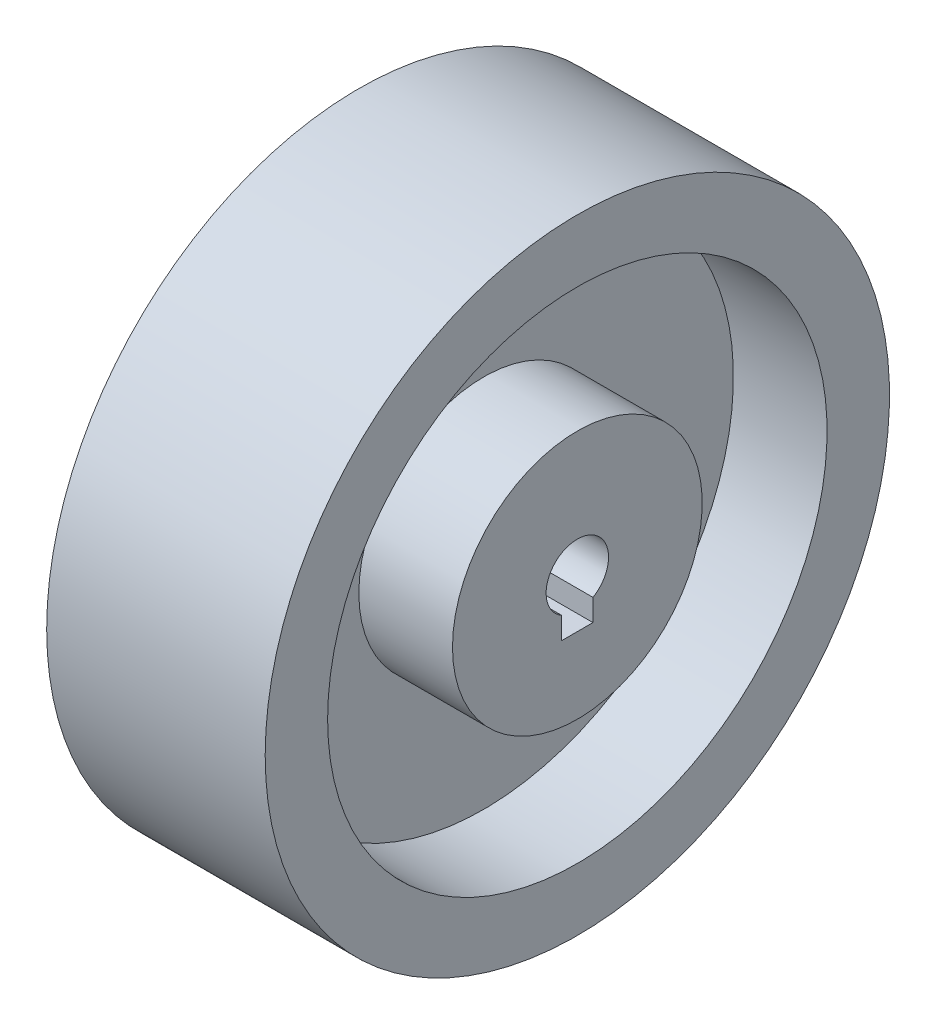
SolidWorks part; units mm, degrees
ref_plane "Front Plane" through (0, 0, 0) normal (0, 0, 1) x (1, 0, 0)
ref_plane "Top Plane" through (0, 0, 0) normal (0, 1, 0) x (1, 0, 0)
ref_plane "Right Plane" through (0, 0, 0) normal (1, 0, 0) x (0, 0, -1)
sketch "Sketch1" plane through (0, 0, 0) normal (0, 0, 1) x (1, 0, 0)
  line L0 (-17.5, 5) -> (-17.5, 0) construction
  line L1 (-17.5, 5) -> (17.5, 5)
  line L2 (17.5, 5) -> (17.5, 20)
  line L3 (17.5, 50) -> (-17.5, 50)
  line L4 (-17.5, 50) -> (-17.5, 40)
  line L5 (-17.5, 40) -> (-2.5, 40)
  line L6 (-2.5, 40) -> (-2.5, 20)
  line L7 (-2.5, 20) -> (-17.5, 20)
  line L8 (0, 50) -> (0, 5) construction
  line L9 (2.5, 20) -> (17.5, 20)
  line L10 (17.5, 40) -> (2.5, 40)
  line L11 (2.5, 40) -> (2.5, 20)
  line L12 (-17.5, 0) -> (17.5, 0) construction
  line L13 (17.5, 0) -> (17.5, 5) construction
  line L14 (17.5, 40) -> (17.5, 50)
  line L15 (-17.5, 20) -> (-17.5, 5)
  dimension "D1" = 35
  dimension "D3" = 15
  dimension "D4" = 45
  dimension "D6" = 5
revolve "Revolve1" add sketch "Sketch1" angle 360 about L12
sketch "Sketch2" plane through (17.5, 0, 0) normal (1, 0, 0) x (0, 0, -1)
  line L0 (0, 0) -> (0, -5) construction
  line L1 (2.5, -4.3301) -> (2.5, -7.8301)
  line L2 (-2.5, -4.3301) -> (-2.5, -7.8301)
  line L3 (-2.5, -7.8301) -> (2.5, -7.8301)
  circle A0 centre (0, 0) radius 5 construction
  arc A1 (-2.5, -4.3301) -> (2.5, -4.3301) centre (0, 0) ccw
  point P9 (0, -7.8301)
  dimension "D1" = 5
  dimension "D2" = 3.5
extrude "Cut-Extrude1" cut sketch "Sketch2" against normal through all contours L3 L1 A1 L2
